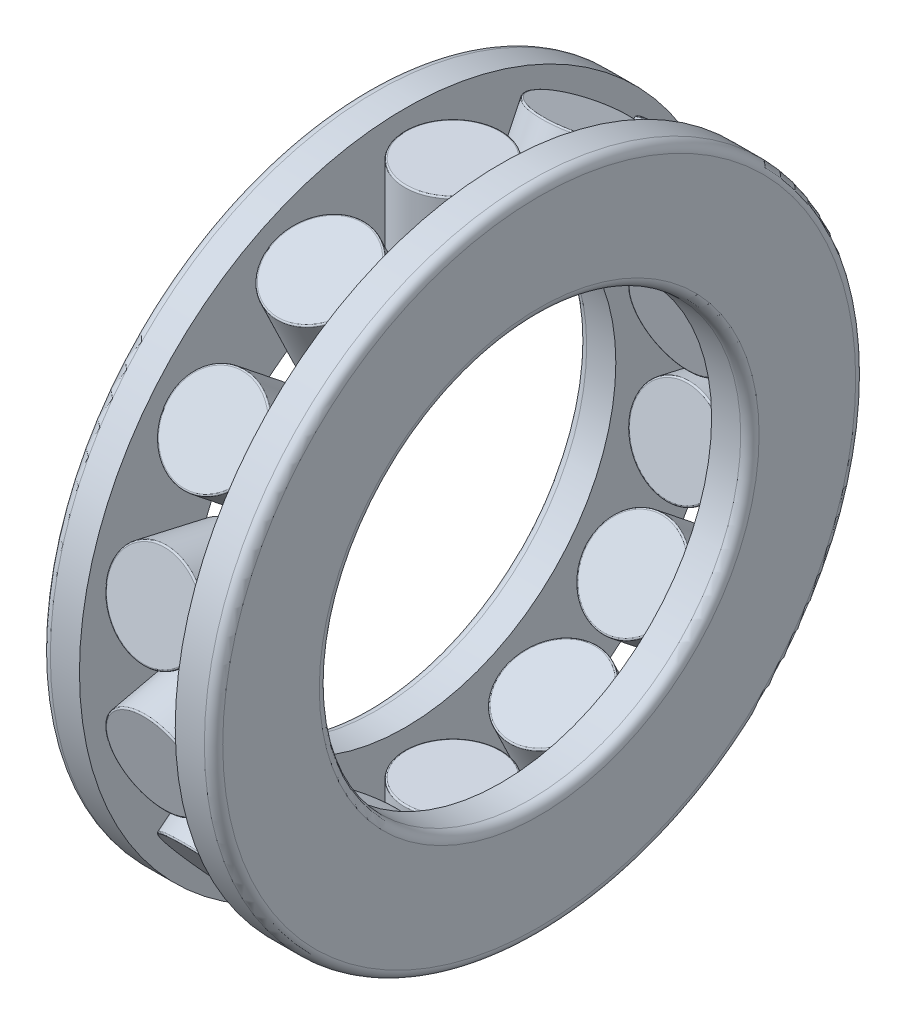
SolidWorks part; units mm, degrees
ref_plane "Plane1" through (0, 0, 0) normal (0, 0, 1) x (1, 0, 0)
ref_plane "Plane2" through (0, 0, 0) normal (0, 1, 0) x (1, 0, 0)
ref_plane "Plane3" through (0, 0, 0) normal (1, 0, 0) x (0, 0, -1)
sketch "Clipboard" plane through (0, 0, 0) normal (0, 0, 1) x (1, 0, 0)
  line L0 (-10, 0) -> (10, 0) construction
  line L1 (0, 0) -> (21.6965, -5.4095)
  line L2 (0, 0) -> (27.3662, 35.0271)
  line L3 (0, 0) -> (13.7666, -17.6205)
  line L4 (0, 0) -> (-22.3471, -0.7804)
  dimension "BallCLRad" = 44.45
  dimension "Count" = 52
  dimension "Show_count" = 52
  dimension "Max_count" = 14
  dimension "Min_count" = 2
sketch "InnRacSke" plane through (0, 0, 0) normal (0, 0, 1) x (1, 0, 0)
  line L1 (-7.9375, 34.925) -> (-12.7635, 34.925)
  line L2 (-14.2875, 36.449) -> (-14.2875, 52.451)
  line L3 (-12.7635, 53.975) -> (-7.9375, 53.975)
  line L4 (-7.9375, 53.975) -> (-7.9375, 34.925)
  line L5 (-34.925, 0) -> (34.925, 0) construction
  line L6 (0, 0) -> (0, 25.4) construction
  arc A0 (-12.7635, 34.925) -> (-14.2875, 36.449) centre (-12.7635, 36.449) cw
  arc A1 (-14.2875, 52.451) -> (-12.7635, 53.975) centre (-12.7635, 52.451) cw
  dimension "ID" = 69.85
  dimension "OD" = 107.95
  dimension "Width" = 28.575
  dimension "gap" = 15.875
revolve "Race" add sketch "InnRacSke" angle 360 about L5
ref_axis "Axis1" through (-50, 0, 0) along (1, 0, 0)
sketch "RolDetSke" plane through (0, 0, 0) normal (0, 0, 1) x (1, 0, 0)
  line L0 (0, 33.02) -> (0, 55.88) construction
  line L3 (0, 50.8) -> (7.7232, 50.8)
  line L4 (0, 50.8) -> (0, 38.1)
  line L5 (0, 38.1) -> (7.7232, 38.1)
  line L6 (7.9772, 50.546) -> (7.9772, 38.354)
  arc A0 (7.9772, 38.354) -> (7.7232, 38.1) centre (7.7232, 38.354) cw
  arc A1 (7.7232, 50.8) -> (7.9772, 50.546) centre (7.7232, 50.546) cw
  dimension "Roller_diameter" = 15.9544
  dimension "Cyl_Len" = 12.7
  dimension "offset" = 38.1
  dimension "D1" = 0.254
revolve "RollerDetailed" add sketch "RolDetSke" angle 360 about L0
sketch "RolSimSke" plane through (0, 0, 0) normal (0, 0, 1) x (1, 0, 0)
  line L1 (-17.78, 0) -> (12.7, 0) construction
  line L3 (-7.7232, 50.8) -> (7.7232, 50.8)
  line L4 (-7.9772, 50.546) -> (-7.9772, 38.354)
  line L5 (-7.7232, 38.1) -> (7.7232, 38.1)
  line L6 (7.9772, 50.546) -> (7.9772, 38.354)
  arc A0 (-7.9772, 38.354) -> (-7.7232, 38.1) centre (-7.7232, 38.354) ccw
  arc A1 (-7.7232, 50.8) -> (-7.9772, 50.546) centre (-7.7232, 50.546) ccw
  arc A2 (7.9772, 50.546) -> (7.7232, 50.8) centre (7.7232, 50.546) ccw
  arc A3 (7.7232, 38.1) -> (7.9772, 38.354) centre (7.7232, 38.354) ccw
  dimension "Rol_rad" = 0.254
  dimension "Roller_diameter" = 15.9544
  dimension "Cyl_Len" = 12.7
  dimension "Halfdia" = 7.9772
  dimension "offset" = 38.1
revolve "RollersSimplified" [suppressed] add sketch "RolSimSke" angle 360 about L1
mirror "Mirror1" about plane through (0, 0, 0) normal (1, 0, 0) of "Race"
pattern_circular "RollersDetailed" count 14 every 25.714 about axis through (-50, 0, 0) along (1, 0, 0) of "RollerDetailed"
sketch "CagSpiSke" plane through (0, 0, 0) normal (0, 0, 1) x (1, 0, 0)
  line L0 (1.9943, 35.2743) -> (1.9943, 53.4352)
  line L1 (1.9943, 53.4352) -> (-1.9943, 53.4352)
  line L3 (-1.9943, 35.2743) -> (1.9943, 35.2743)
  line L4 (-34.925, 0) -> (34.925, 0) construction
  line L5 (0, 0) -> (0, 60.773) construction
  line L6 (-1.9943, 35.2743) -> (-1.9943, 53.4352)
  dimension "ID" = 70.5485
  dimension "OD" = 106.8705
  dimension "Thickness" = 3.9886
revolve "CageSpine" [suppressed] add sketch "CagSpiSke" angle 360 about L4
equation "\"BallCLRad@Clipboard\" =  ( \"OD@InnRacSke\" + \"ID@InnRacSke\" )  / 4"
equation "\"Cyl_Len@RolSimSke\" = \"Cyl_Len@RolDetSke\""
equation "\"offset@RolSimSke\" = \"BallCLRad@Clipboard\" - \"Cyl_Len@RolSimSke\" / 2"
equation "\"offset@RolDetSke\" = \"BallCLRad@Clipboard\" - \"Cyl_Len@RolDetSke\" / 2"
equation "\"Roller_diameter@RolDetSke\" = \"gap@InnRacSke\" * 1.005"
equation "\"Roller_diameter@RolSimSke\" = \"gap@InnRacSke\" * 1.005"
equation "\"Max_count@Clipboard\" = int( 3.14159265 / atn(( \"Roller_diameter@RolDetSke\" / 2) / sqr( \"offset@RolDetSke\"  *  \"offset@RolDetSke\" - ( \"Roller_diameter@RolDetSke\" / 2) *  ( \"Roller_diameter@RolDetSke\" / 2))))"
equation "\"Max_count@Clipboard\" = ((sgn( \"Max_count@Clipboard\" - \"Count@Clipboard\" )-1)*( \"Max_count@Clipboard\" - \"Count@Clipboard\" ))/-2+ \"Count@Clipboard\""
equation "\"Count@RollersDetailed\" = int( \"Show_count@Clipboard\" ) "
equation "\"Count@RollersDetailed\" = ((sgn( \"Count@RollersDetailed\" - \"Max_count@Clipboard\" )-1)*( \"Count@RollersDetailed\" - \"Max_count@Clipboard\" ))/-2+ \"Max_count@Clipboard\""
equation "\"Count@RollersDetailed\" = ((sgn( \"Count@RollersDetailed\" - \"Min_count@Clipboard\" )+1)*( \"Count@RollersDetailed\" - \"Min_count@Clipboard\"))/2 +\"Min_count@Clipboard\""
equation "\"Angle@RollersDetailed\" = 360.0 / \"Max_count@Clipboard\""
equation "\"Angle@CageSpine\" =  \"Angle@RollersDetailed\" * ( \"Count@RollersDetailed\" -1 + int( \"Count@RollersDetailed\" / \"Max_count@Clipboard\" ) )  + 0.001 -  int( \"Count@RollersDetailed\" / \"Max_count@Clipboard\" ) * 0.001"
equation "\"Angle@CageSpine\" =  \"Angle@CageSpine\" * int( \"Min_count@Clipboard\" / 2) + int(1 / \"Min_count@Clipboard\")  * 0.001"
equation "\"Thickness@CagSpiSke\" =  \"Roller_diameter@RolDetSke\" * 0.25"
equation "\"OD@CagSpiSke\" = \"OD@InnRacSke\" * 0.99"
equation "\"ID@CagSpiSke\" = \"ID@InnRacSke\" * 1.01"
equation "\"Halfdia@RolSimSke\" = \"Roller_diameter@RolSimSke\" / 2"
